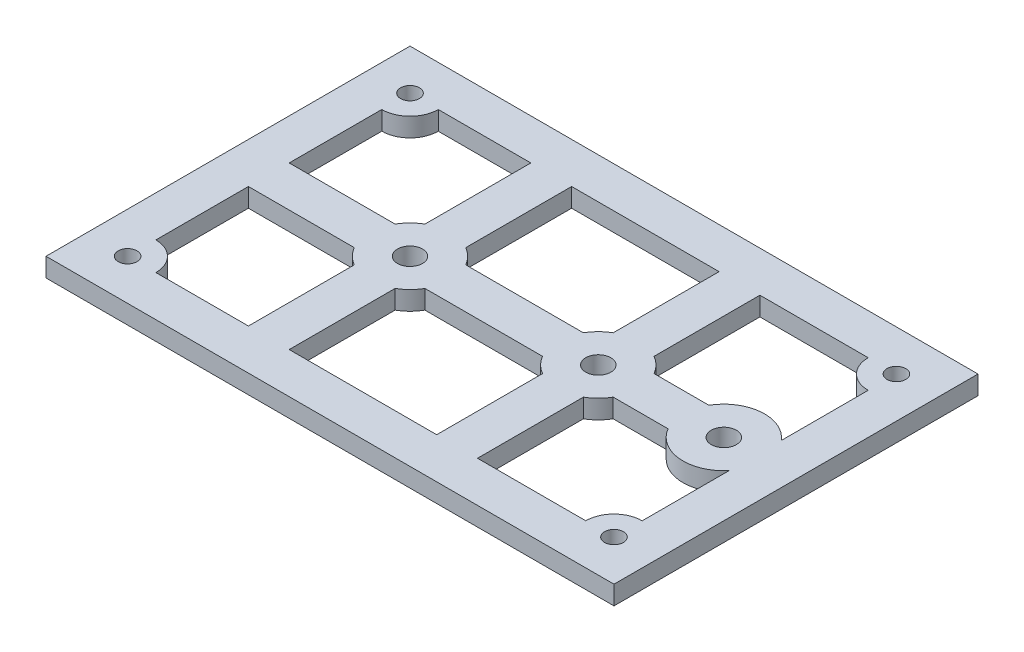
SolidWorks part; units mm, degrees
ref_plane "Front Plane" through (0, 0, 0) normal (0, 0, 1) x (1, 0, 0)
ref_plane "Top Plane" through (0, 0, 0) normal (0, 1, 0) x (1, 0, 0)
ref_plane "Right Plane" through (0, 0, 0) normal (1, 0, 0) x (0, 0, -1)
sketch "Sketch1" plane through (0, 0, 0) normal (0, 1, 0) x (1, 0, 0)
  line L5 (-52.5, 22.5) -> (25, 22.5)
  line L6 (-52.5, 22.5) -> (-52.5, -22.5)
  line L7 (-52.5, -22.5) -> (25, -22.5)
  line L8 (25, 22.5) -> (25, -22.5)
  circle A0 centre (-30, 0) radius 22.5
  circle A1 centre (0, 0) radius 15
  circle A2 centre (20, 0) radius 5
  circle A3 centre (0, 0) radius 7.5
  point P0 (0, 0)
  dimension "D3" = 45
  dimension "D4" = 30
  dimension "D5" = 10
  dimension "D1" = 15
extrude "Boss-Extrude1" add sketch "Sketch1" along normal blind 3 contours A2 L8 L5 A0 A1 | A2 A1 A0 L7 L8 | A0 L5 L6 | A0 L6 L7 | A3 | A2 | A0 A3 A1 | A1 A0 | A0 A1
sketch "Sketch3" plane through (0, 3, 0) normal (0, 1, 0) x (1, 0, 0)
  line L1 (-52.5, 22.5) -> (25, 22.5)
  line L2 (-52.5, 22.5) -> (-52.5, -22.5)
  line L3 (-52.5, -22.5) -> (25, -22.5)
  line L4 (25, 22.5) -> (25, -22.5)
  line L5 (-59, 29) -> (31.5, 29)
  line L6 (-59, 29) -> (-59, -29)
  line L7 (-59, -29) -> (31.5, -29)
  line L8 (31.5, 29) -> (31.5, -29)
  dimension "D1" = 6.5
  dimension "D2" = 6.5
  dimension "D3" = 6.5
  dimension "D4" = 6.5
extrude "Boss-Extrude2" add sketch "Sketch3" against normal blind 3
sketch "Sketch2" plane through (0, 3, 0) normal (0, 1, 0) x (1, 0, 0)
  line L0 (-13.75, -29) -> (-13.75, 29) construction
  line L3 (-59, 0) -> (31.5, 0) construction
  line L4 (3.25, -22.5) -> (3.25, -5.6292)
  line L6 (0, -29) -> (0, 29) construction
  line L7 (-3.25, -22.5) -> (-3.25, -5.6292)
  line L8 (20.5, -22.5) -> (3.25, -22.5)
  line L9 (-5.6292, -3.25) -> (-24.3708, -3.25)
  line L11 (-3.25, -22.5) -> (-26.75, -22.5)
  line L12 (25, -18) -> (25, -4.1533)
  line L13 (-3.25, 22.5) -> (-26.75, 22.5)
  line L14 (-3.25, 22.5) -> (-3.25, 5.6292)
  line L15 (3.25, 22.5) -> (3.25, 5.6292)
  line L16 (20.5, 22.5) -> (3.25, 22.5)
  line L17 (-5.6292, 3.25) -> (-24.3708, 3.25)
  line L20 (-26.75, -22.5) -> (-26.75, -5.6292)
  line L24 (-26.75, 22.5) -> (-26.75, 5.6292)
  line L25 (-48, 22.5) -> (-33.25, 22.5)
  line L26 (-33.25, 22.5) -> (-33.25, 5.6292)
  line L27 (-33.25, -22.5) -> (-33.25, -5.6292)
  line L28 (-48, -22.5) -> (-33.25, -22.5)
  line L29 (-52.5, -18) -> (-52.5, -3.25)
  line L30 (-35.6292, -3.25) -> (-52.5, -3.25)
  line L31 (-35.6292, 3.25) -> (-52.5, 3.25)
  line L32 (-52.5, 3.25) -> (-52.5, 18)
  line L33 (5.6292, 3.25) -> (14.3708, 3.25)
  line L34 (5.6292, -3.25) -> (14.3708, -3.25)
  line L35 (25, 4.1533) -> (25, 18)
  line L37 (-33.25, 14.0646) -> (-26.75, 14.0646) construction
  line L39 (31.5, -29) -> (31.5, 29) construction
  line L40 (-59, -29) -> (31.5, -29) construction
  line L41 (-59, 29) -> (-59, -29) construction
  line L42 (31.5, 29) -> (-59, 29) construction
  arc A0 (3.25, -5.6292) -> (5.6292, -3.25) centre (0, 0) ccw
  arc A4 (20.5, -22.5) -> (25, -18) centre (25, -22.5) cw
  arc A6 (-5.6292, -3.25) -> (-3.25, -5.6292) centre (0, 0) ccw
  arc A7 (-3.25, 5.6292) -> (-5.6292, 3.25) centre (0, 0) ccw
  arc A8 (20.5, 22.5) -> (25, 18) centre (25, 22.5) ccw
  arc A9 (-24.3708, -3.25) -> (-26.75, -5.6292) centre (-30, 0) cw
  arc A10 (-26.75, 5.6292) -> (-24.3708, 3.25) centre (-30, 0) cw
  arc A11 (-33.25, -5.6292) -> (-35.6292, -3.25) centre (-30, 0) cw
  arc A12 (-48, -22.5) -> (-52.5, -18) centre (-52.5, -22.5) ccw
  arc A13 (-48, 22.5) -> (-52.5, 18) centre (-52.5, 22.5) cw
  arc A14 (-35.6292, 3.25) -> (-33.25, 5.6292) centre (-30, 0) cw
  arc A15 (5.6292, 3.25) -> (3.25, 5.6292) centre (0, 0) ccw
  circle A16 centre (0, 0) radius 2
  circle A17 centre (-30, 0) radius 2
  circle A18 centre (25, -22.5) radius 1.5
  circle A19 centre (-52.5, -22.5) radius 1.5
  circle A20 centre (-52.5, 22.5) radius 1.5
  circle A21 centre (25, 22.5) radius 1.5
  arc A23 (14.3708, -3.25) -> (25, -4.1533) centre (20, 0) ccw
  circle A24 centre (20, 0) radius 2
  arc A25 (25, 4.1533) -> (14.3708, 3.25) centre (20, 0) ccw
  dimension "D3" = 6.5
  dimension "D8" = 9
  dimension "D4" = 6.5
  dimension "D5" = 6.5
  dimension "D6" = 4
  dimension "D7" = 3
  dimension "D10" = 6.5
  dimension "D11" = 22.5
  dimension "D13" = 5
  dimension "D14" = 4
  dimension "D15" = 13
  dimension "D2" = 6.5
  dimension "D9" = 6.5
  dimension "D12" = 6.5
  dimension "D16" = 6.5
extrude "Cut-Extrude1" cut sketch "Sketch2" against normal blind 3 contours L24 A10 L17 A7 L14 L13 | L9 A9 L20 L11 L7 A6 | A12 L28 L27 A11 L30 L29 | A25 L35 A8 L16 L15 A15 L33 | A23 L34 A0 L4 L8 A4 L12 | L32 A13 L25 L26 A14 L31 | A20 | A17 | A16 | A21 | A24 | A18 | A19
